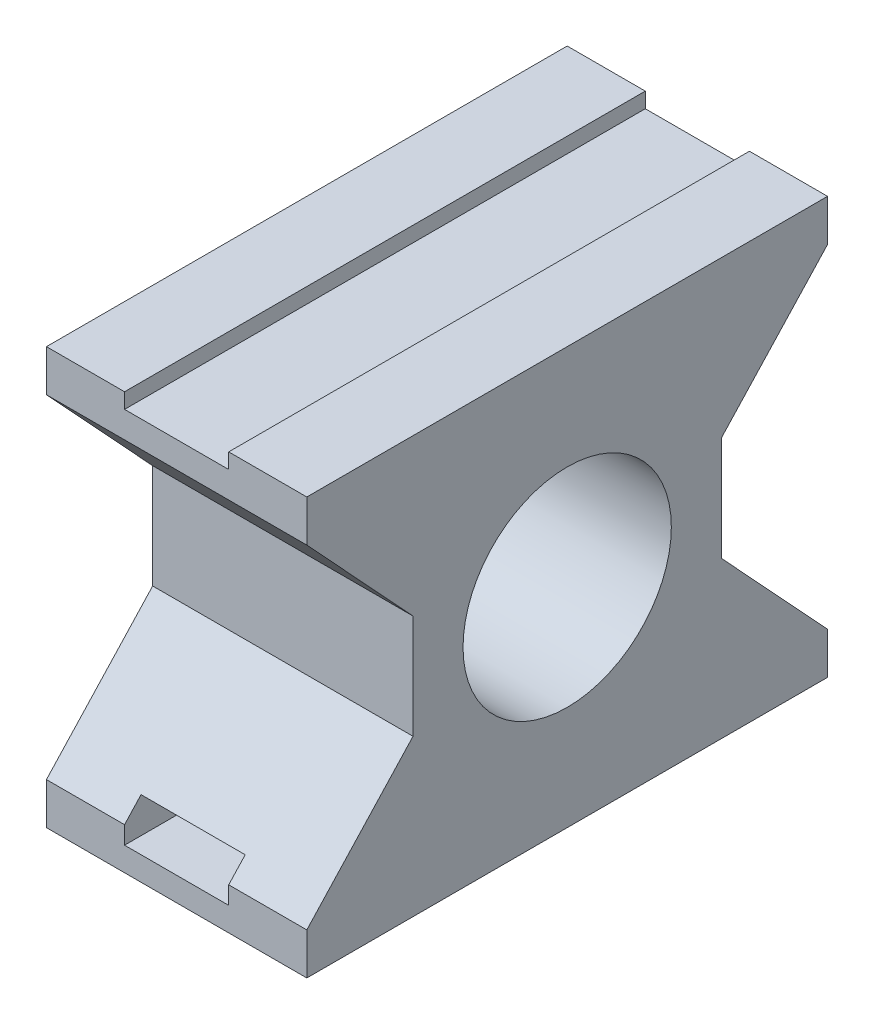
SolidWorks part; units mm, degrees
ref_plane "Front Plane" through (0, 0, 0) normal (0, 0, 1) x (1, 0, 0)
ref_plane "Top Plane" through (0, 0, 0) normal (0, 1, 0) x (1, 0, 0)
ref_plane "Right Plane" through (0, 0, 0) normal (1, 0, 0) x (0, 0, -1)
sketch "Sketch1" plane through (0, 0, 0) normal (1, 0, 0) x (0, 0, -1)
  line L0 (29.5249, 40.7131) -> (-70.4751, 40.7131)
  line L1 (-70.4751, 40.7131) -> (-70.4751, 32.7131)
  line L2 (-70.4751, 32.7131) -> (-50.079, 10.7131)
  line L3 (-50.079, 10.7131) -> (-50.079, -9.2869)
  line L4 (-50.079, -9.2869) -> (-70.4751, -31.2869)
  line L5 (-70.4751, -31.2869) -> (-70.4751, -39.2869)
  line L6 (-70.4751, -39.2869) -> (29.5249, -39.2869)
  line L7 (-20.4751, -39.2869) -> (-20.4751, 40.7131) construction
  line L8 (29.5249, -31.2869) -> (29.5249, -39.2869)
  line L9 (9.1288, -9.2869) -> (29.5249, -31.2869)
  line L10 (9.1288, 10.7131) -> (9.1288, -9.2869)
  line L11 (29.5249, 32.7131) -> (9.1288, 10.7131)
  line L12 (29.5249, 40.7131) -> (29.5249, 32.7131)
  circle A0 centre (-20.4751, 0.7131) radius 20
  dimension "D8" = 40
  dimension "D1" = 8
  dimension "D2" = 30
  dimension "D3" = 30
  dimension "D4" = 20
  dimension "D5" = 80
  dimension "D6" = 50
  dimension "D7" = 30
extrude "Boss-Extrude1" add sketch "Sketch1" along normal blind 50
sketch "Sketch2" plane through (0, 0, 70.4751) normal (0, 0, 1) x (1, 0, 0)
  line L0 (50, 40.7131) -> (0, 40.7131) construction
  line L1 (15, 43.6469) -> (35, 43.6469)
  line L2 (15, 43.6469) -> (15, 37.7794)
  line L3 (15, 37.7794) -> (35, 37.7794)
  line L4 (35, 43.6469) -> (35, 37.7794)
  line L5 (15, 43.6469) -> (35, 37.7794) construction
  line L6 (15, 37.7794) -> (35, 43.6469) construction
  line L7 (50, -31.2869) -> (0, -31.2869) construction
  line L8 (15, -27.8721) -> (35, -27.8721)
  line L9 (15, -27.8721) -> (15, -34.7017)
  line L10 (15, -34.7017) -> (35, -34.7017)
  line L11 (35, -27.8721) -> (35, -34.7017)
  line L12 (15, -27.8721) -> (35, -34.7017) construction
  line L13 (15, -34.7017) -> (35, -27.8721) construction
  point P0 (25, 40.7131)
  point P7 (25, -31.2869)
  dimension "D1" = 20
  dimension "D2" = 20
extrude "Cut-Extrude1" cut sketch "Sketch2" against normal through all
